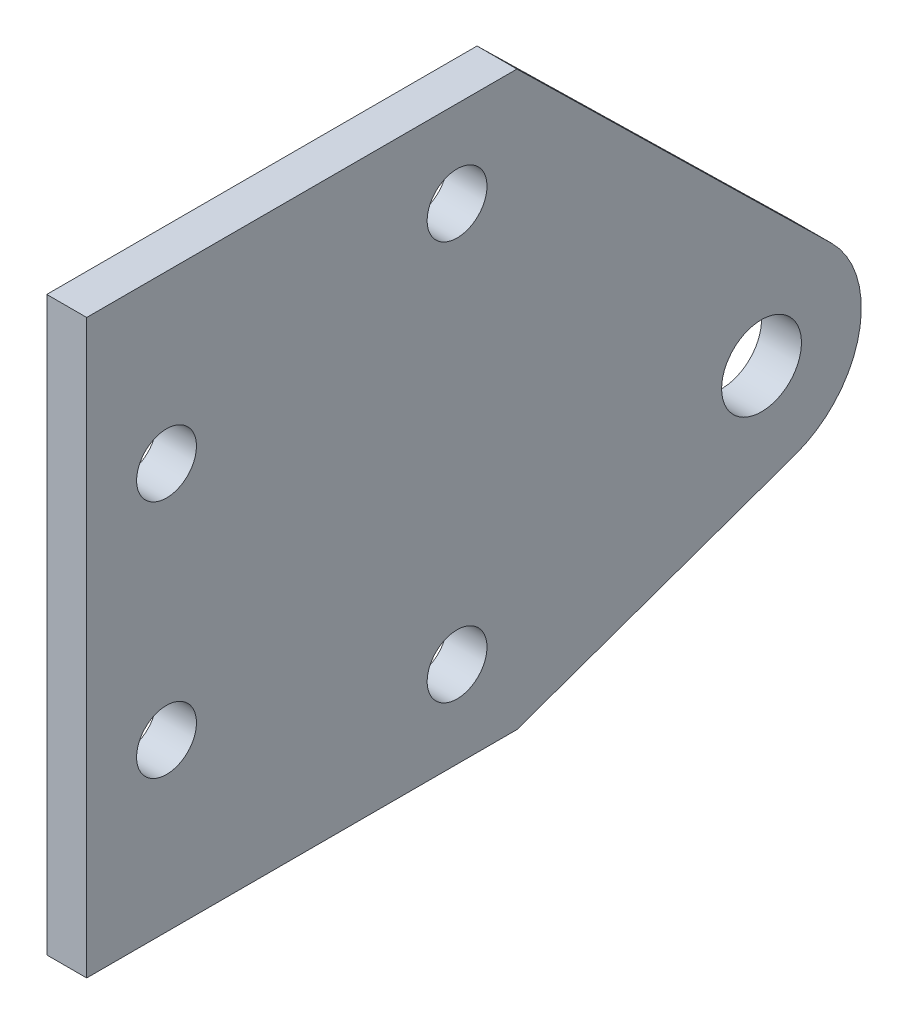
SolidWorks part; units mm, degrees
ref_plane "Front Plane" through (0, 0, 0) normal (0, 0, 1) x (1, 0, 0)
ref_plane "Top Plane" through (0, 0, 0) normal (0, 1, 0) x (1, 0, 0)
ref_plane "Right Plane" through (0, 0, 0) normal (1, 0, 0) x (0, 0, -1)
sketch "Sketch1" plane through (-25.4, 0, 0) normal (-1, 0, 0) x (0, 0, 1)
  line L6 (-88.4975, 379.3607) -> (-113.504, 354.8689) construction
  line L9 (-88.4975, 379.3607) -> (-113.504, 354.8689)
  line L24 (-103.0725, 379.3607) -> (-103.0725, 365.0857)
  line L25 (-103.0725, 379.3607) -> (-103.0725, 365.0857)
  line L26 (-54.275, 379.3607) -> (-103.0725, 379.3607)
  line L27 (-103.0725, 365.0857) -> (-113.504, 354.8689)
  line L28 (-110.6082, 341.719) -> (-88.4975, 333.8607)
  line L29 (-88.4975, 333.8607) -> (-54.275, 333.8607)
  line L30 (-54.275, 333.8607) -> (-54.275, 379.3607)
  line L31 (-54.275, 379.3607) -> (-103.0725, 379.3607)
  line L32 (-103.0725, 365.0857) -> (-113.504, 354.8689)
  line L33 (-110.6082, 341.719) -> (-88.4975, 333.8607)
  line L34 (-88.4975, 333.8607) -> (-54.275, 333.8607)
  line L35 (-54.275, 333.8607) -> (-54.275, 379.3607)
  circle A1 centre (-83.735, 372.4857) radius 2.3813 construction
  circle A2 centre (-83.735, 340.7357) radius 2.3813 construction
  circle A3 centre (-60.625, 366.1357) radius 2.3813 construction
  circle A4 centre (-60.625, 347.0857) radius 2.3813 construction
  circle A6 centre (-83.735, 372.4857) radius 2.3813
  circle A7 centre (-83.735, 340.7357) radius 2.3813
  circle A8 centre (-60.625, 366.1357) radius 2.3813
  circle A9 centre (-60.625, 347.0857) radius 2.3813
  circle A13 centre (-107.95, 349.1982) radius 3.175
  circle A14 centre (-107.95, 349.1982) radius 3.175
  arc A15 (-113.504, 354.8689) -> (-110.6082, 341.719) centre (-107.95, 349.1982) ccw
  arc A16 (-113.504, 354.8689) -> (-110.6082, 341.719) centre (-107.95, 349.1982) ccw
  circle M7 centre (-60.625, 347.0857) radius 3.2639
  circle M8 centre (-83.735, 340.7357) radius 3.2639
  line M9 (-54.275, 379.3607) -> (-88.4975, 379.3607)
  line M10 (-88.4975, 379.3607) -> (-102.0374, 362.628)
  arc M11 (-102.0374, 362.628) -> (-102.1959, 351.8452) centre (-95.25, 357.1357) ccw
  line M12 (-102.1959, 351.8452) -> (-88.4975, 333.8607)
  line M13 (-88.4975, 333.8607) -> (-54.275, 333.8607)
  line M14 (-54.275, 333.8607) -> (-54.275, 379.3607)
  circle M15 centre (-95.25, 357.1357) radius 3.9687
  circle M16 centre (-83.735, 372.4857) radius 3.2639
  circle M17 centre (-60.625, 366.1357) radius 3.2639
  dimension "D1" = 0
  dimension "D2" = 0
extrude "Boss-Extrude1" add sketch "Sketch1" along normal blind 3.175 contours L9 A16 L33 A14 M12 M11 M10 | M14 M9 M10 M11 M12 M13 M8 M15 M17 M16 M7 | M15 | A8 M17 | A6 M16 | A9 M7 | A7 M8
